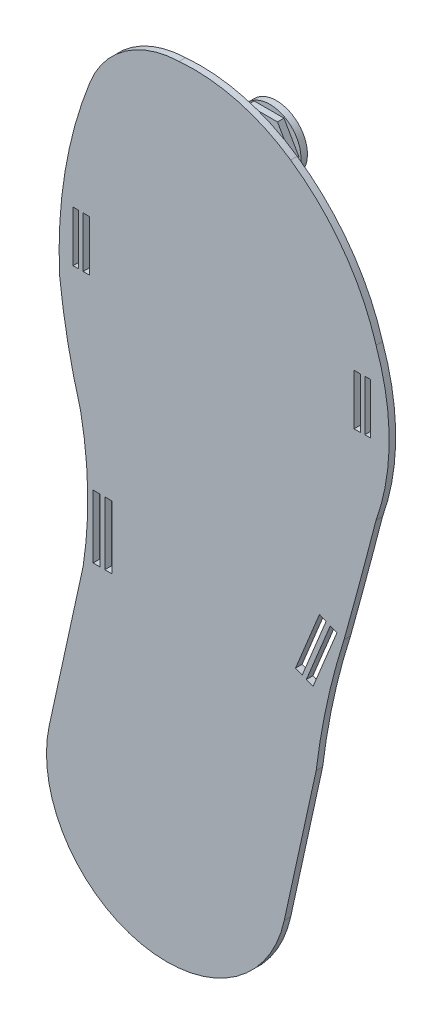
SolidWorks part; units mm, degrees
ref_plane "Front Plane" through (0, 0, 0) normal (0, 0, 1) x (1, 0, 0)
ref_plane "Top Plane" through (0, 0, 0) normal (0, 1, 0) x (1, 0, 0)
ref_plane "Right Plane" through (0, 0, 0) normal (1, 0, 0) x (0, 0, -1)
sketch "Sketch1" plane through (0, 0, 0) normal (0, 0, 1) x (1, 0, 0)
  line L0 (746.4018, 685.1437) -> (1343.7351, 685.1437) construction
  line L1 (-51.9841, 392.7496) -> (0, 630.0981)
  line L2 (308.9904, 313.6889) -> (358.0638, 537.7476)
  arc A0 (-51.9841, 392.7496) -> (308.9904, 313.6889) centre (128.5031, 353.2192) ccw
  arc A1 (0, 630.0981) -> (-3.9841, 836.2782) centre (-582.9992, 721.9612) ccw
  arc A2 (358.0638, 537.7476) -> (400.9081, 733.3643) centre (1416.031, 408.5298) cw
  arc A3 (-3.9841, 836.2782) -> (-36.0126, 998.5024) centre (912.2213, 1101.4418) cw
  arc A4 (-36.0126, 998.5024) -> (10.5352, 1279.7162) centre (634.3449, 1032.001) cw
  arc A5 (400.9081, 733.3643) -> (450.0332, 916.6956) centre (-9292.1389, 3428.9398) ccw
  arc A6 (450.0332, 916.6956) -> (450.0332, 1149.5484) centre (124.6316, 1033.122) ccw
  arc A7 (450.0332, 1149.5484) -> (318.8388, 1330.4675) centre (127.1501, 1053.4358) ccw
  arc A8 (10.5352, 1279.7162) -> (147.4353, 1375.9125) centre (152.355, 1223.3994) cw
  arc A9 (147.4353, 1375.9125) -> (318.8388, 1330.4675) centre (170.1313, 1115.5528) cw
  dimension "D3" = 1065.8292
  dimension "D4" = 10060.8791
  dimension "D5" = 509.7133
  dimension "D6" = 336.8844
  dimension "D1" = 369.531
  dimension "D2" = 224.0587
extrude "Boss-Extrude1" add sketch "Sketch1" along normal blind 10
sketch "Sketch3" plane through (0, 0, 0) normal (0, 0, -1) x (-1, 0, 0)
  line L1 (0, 1100.7189) -> (-9.5652, 1100.7189)
  line L2 (0, 1100.7189) -> (0, 1022.7525)
  line L3 (0, 1022.7525) -> (-9.5652, 1022.7525)
  line L4 (-9.5652, 1100.7189) -> (-9.5652, 1022.7525)
  line L5 (7, 1100.7189) -> (15.3535, 1100.7189)
  line L6 (7, 1100.7189) -> (7, 1022.7525)
  line L7 (7, 1022.7525) -> (15.3535, 1022.7525)
  line L8 (15.3535, 1100.7189) -> (15.3535, 1022.7525)
  line L9 (-441.1961, 1099.8605) -> (-441.1961, 1021.894)
  line L10 (-432.8425, 1021.894) -> (-441.1961, 1021.894)
  line L11 (-432.8425, 1099.8605) -> (-432.8425, 1021.894)
  line L12 (-432.8425, 1099.8605) -> (-441.1961, 1099.8605)
  line L13 (-416.2773, 1099.4312) -> (-416.2773, 1021.4648)
  line L14 (-425.8425, 1021.4648) -> (-416.2773, 1021.4648)
  line L15 (-425.8425, 1099.4312) -> (-425.8425, 1021.4648)
  line L16 (-425.8425, 1099.4312) -> (-416.2773, 1099.4312)
  dimension "D1" = 7
  dimension "D2" = 7
extrude "Cut-Extrude1" cut sketch "Sketch3" against normal blind 250
sketch "Sketch4" plane through (0, 0, 0) normal (0, 0, -1) x (-1, 0, 0)
  line L0 (-44.333, 642.5598) -> (-33.333, 642.5598)
  line L1 (-26.333, 739.5598) -> (-15.333, 739.5598)
  line L2 (-26.333, 739.5598) -> (-26.333, 642.5598)
  line L4 (-15.333, 739.5598) -> (-15.333, 642.5598)
  line L5 (-33.333, 739.5598) -> (-44.333, 739.5598)
  line L6 (-33.333, 739.5598) -> (-33.333, 642.5598)
  line L8 (-44.333, 739.5598) -> (-44.333, 642.5598)
  line L9 (-363.1242, 747.9664) -> (-326.394, 658.1895)
  line L10 (-336.5749, 654.0242) -> (-326.394, 658.1895)
  line L11 (-373.3051, 743.8011) -> (-336.5749, 654.0242)
  line L12 (-373.3051, 743.8011) -> (-363.1242, 747.9664)
  line L13 (-389.9522, 736.9547) -> (-353.222, 647.1778)
  line L14 (-343.0412, 651.343) -> (-353.222, 647.1778)
  line L15 (-379.7713, 741.1199) -> (-343.0412, 651.343)
  line L16 (-379.7713, 741.1199) -> (-389.9522, 736.9547)
  line L17 (-26.333, 642.5598) -> (-15.333, 642.5598)
  dimension "D1" = 97
  dimension "D2" = 97
  dimension "D3" = 11
  dimension "D4" = 11
  dimension "D5" = 7
  dimension "D6" = 7
extrude "Cut-Extrude2" cut sketch "Sketch4" against normal blind 250
sketch "Sketch5" plane through (0, 0, 0) normal (0, 0, -1) x (-1, 0, 0)
  circle A0 centre (-145.6873, 1201.3284) radius 25
extrude "Boss-Extrude2" add sketch "Sketch5" along normal blind 120
sketch "Sketch6" plane through (0, 0, -120) normal (0, 0, -1) x (-1, 0, 0)
  line L1 (-99.8231, 1201.3284) -> (-122.7552, 1241.048)
  line L2 (-122.7552, 1241.048) -> (-168.6194, 1241.048)
  line L3 (-168.6194, 1241.048) -> (-191.5515, 1201.3284)
  line L4 (-191.5515, 1201.3284) -> (-168.6194, 1161.6089)
  line L5 (-168.6194, 1161.6089) -> (-122.7552, 1161.6089)
  line L6 (-122.7552, 1161.6089) -> (-99.8231, 1201.3284)
  circle A0 centre (-145.6873, 1201.3284) radius 39.7196 construction
extrude "Boss-Extrude3" add sketch "Sketch6" along normal blind 10
sketch "Sketch10" plane through (0, 0, -130) normal (0, 0, -1) x (-1, 0, 0)
  circle A0 centre (-146.996, 1200.9615) radius 47.6875
extrude "Boss-Extrude4" add sketch "Sketch10" along normal blind 10
